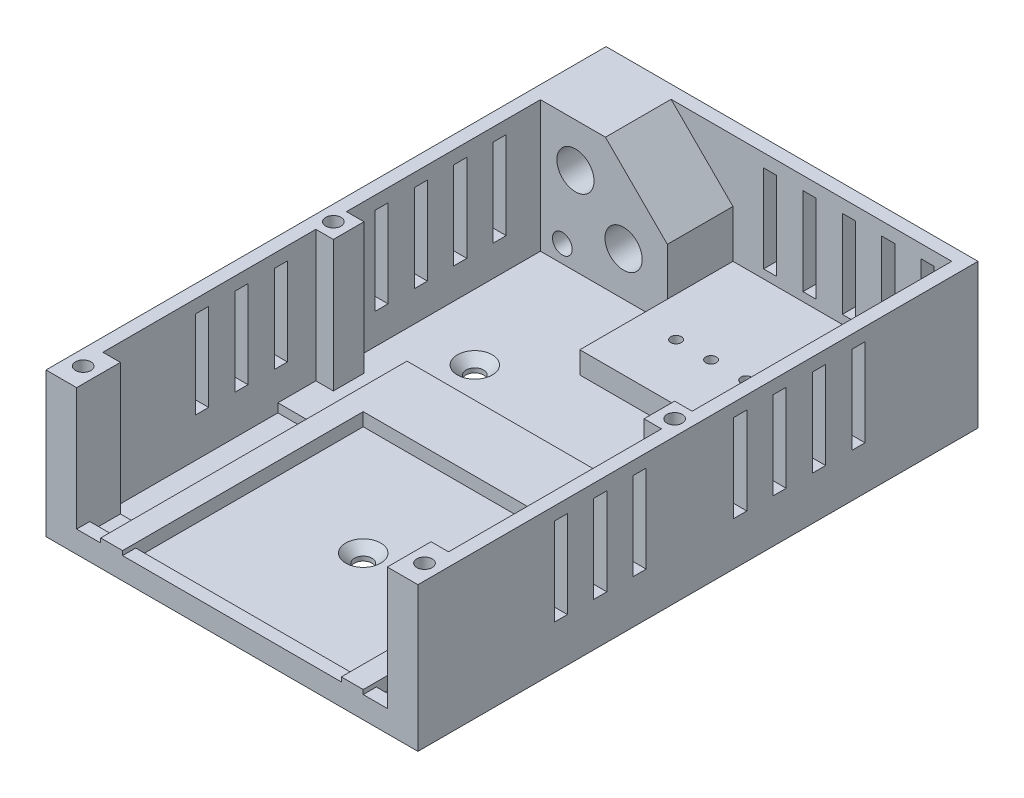
SolidWorks part; units mm, degrees
ref_plane "Front Plane" through (0, 0, 0) normal (0, 0, 1) x (1, 0, 0)
ref_plane "Top Plane" through (0, 0, 0) normal (0, 1, 0) x (1, 0, 0)
ref_plane "Right Plane" through (0, 0, 0) normal (1, 0, 0) x (0, 0, -1)
sketch "Sketch2" plane through (0, 0, 0) normal (0, 1, 0) x (1, 0, 0)
  line L1 (39.5, -62.5) -> (-39.5, -62.5)
  line L2 (39.5, -62.5) -> (39.5, 62.5)
  line L3 (39.5, 62.5) -> (-39.5, 62.5)
  line L4 (-39.5, -62.5) -> (-39.5, 62.5)
  line L5 (39.5, -62.5) -> (-39.5, 62.5) construction
  line L6 (39.5, 62.5) -> (-39.5, -62.5) construction
  point P0 (0, 0)
  dimension "D1" = 79
  dimension "D2" = 125
extrude "Boss-Extrude1" add sketch "Sketch2" along normal blind 3
sketch "Sketch9" plane through (0, 0, 0) normal (0, 1, 0) x (1, 0, 0)
  line L2 (-39.5, 62.5) -> (-39.5, -62.5)
  line L3 (-39.5, -62.5) -> (-42.5, -62.5)
  line L4 (-42.5, 65.5) -> (-42.5, -62.5)
  line L6 (39.5, 62.5) -> (39.5, -62.5)
  line L7 (39.5, -62.5) -> (42.5, -62.5)
  line L8 (42.5, 65.5) -> (42.5, -62.5)
  line L9 (39.5, 62.5) -> (-39.5, 62.5)
  line L11 (42.5, 65.5) -> (-42.5, 65.5)
  dimension "D1" = 3
  dimension "D2" = 3
  dimension "D3" = 3
sketch "Sketch3" plane through (0, 3, 0) normal (0, 1, 0) x (1, 0, 0)
  line L0 (0, -62.5) -> (0, 62.5) construction
  line L1 (-39.5, -62.5) -> (39.5, -62.5) construction
  line L2 (39.5, 62.5) -> (-39.5, 62.5) construction
  line L4 (30, -62.5) -> (-30, -62.5)
  line L5 (30, -62.5) -> (30, 7.5)
  line L6 (30, 7.5) -> (-30, 7.5)
  line L7 (-30, -62.5) -> (-30, 7.5)
  line L8 (30, -62.5) -> (-30, 7.5) construction
  line L9 (30, 7.5) -> (-30, -62.5) construction
  point P6 (0, -27.5)
  dimension "D1" = 60
  dimension "D2" = 70
extrude "support" add sketch "Sketch3" along normal blind 3
sketch "Sketch4" plane through (0, 6, 0) normal (0, 1, 0) x (1, 0, 0)
  line L0 (-30, -62.5) -> (30, -62.5) construction
  line L1 (-25, -62.5) -> (25, -62.5)
  line L2 (-25, -62.5) -> (-25, -7.5)
  line L3 (-25, -7.5) -> (25, -7.5)
  line L4 (25, -62.5) -> (25, -7.5)
  line L5 (30, 7.5) -> (-30, 7.5) construction
  line L6 (30, -62.5) -> (30, 7.5) construction
  line L7 (-30, 7.5) -> (-30, -62.5) construction
  dimension "D1" = 15
  dimension "D2" = 5
  dimension "D3" = 5
extrude "remove plastic" cut sketch "Sketch4" against normal blind 3
sketch "Sketch5" plane through (0, 3, 0) normal (0, 1, 0) x (1, 0, 0)
  line L1 (-10.5, 62.5) -> (39.5, 62.5)
  line L2 (-10.5, 62.5) -> (-10.5, 27.5)
  line L3 (-10.5, 27.5) -> (39.5, 27.5)
  line L4 (39.5, 62.5) -> (39.5, 27.5)
  line L5 (39.5, -62.5) -> (39.5, 62.5) construction
  line L7 (30, -62.5) -> (39.5, -62.5) construction
  line L8 (39.5, 62.5) -> (-39.5, 62.5) construction
  dimension "D1" = 50
  dimension "D3" = 90
extrude "Boss-Extrude3" add sketch "Sketch5" along normal blind 5
sketch "Sketch6" plane through (0, 8, 0) normal (0, 1, 0) x (1, 0, 0)
  line L0 (-10.5, 40.5) -> (39.5, 40.5) construction
  line L3 (14.5, 62.5) -> (14.5, 27.5) construction
  line L4 (39.5, 62.5) -> (-10.5, 62.5) construction
  line L5 (-10.5, 27.5) -> (39.5, 27.5) construction
  line L8 (-10.5, 27.5) -> (39.5, 27.5) construction
  circle A0 centre (-1.5, 40.5) radius 1.2
  circle A1 centre (6.5, 40.5) radius 1.2
  circle A2 centre (14.5, 40.5) radius 1.2
  circle A3 centre (22.5, 40.5) radius 1.2
  circle A4 centre (30.5, 40.5) radius 1.2
  dimension "D1" = 2.4
  dimension "D2" = 8
  dimension "D3" = 8
  dimension "D4" = 8
  dimension "D5" = 8
  dimension "D6" = 13
extrude "Cut-Extrude2" cut sketch "Sketch6" against normal blind 5 draft 1
sketch "Sketch7" plane through (0, 3, 0) normal (0, 1, 0) x (1, 0, 0)
  line L0 (-39.5, 62.5) -> (-39.5, -62.5) construction
  line L1 (-10.5, 62.5) -> (-39.5, 62.5)
  line L2 (-10.5, 62.5) -> (-10.5, 47.5)
  line L3 (-10.5, 47.5) -> (-39.5, 47.5)
  line L4 (-39.5, 62.5) -> (-39.5, 47.5)
  dimension "D1" = 15
extrude "cable block" add sketch "Sketch7" along normal blind 30
extrude "walls" add sketch "Sketch9" along normal up to surface (33 mm away) up to face at (-25, 33, -55)
sketch "Sketch8" plane through (0, 0, -47.5) normal (0, 0, 1) x (1, 0, 0)
  line L0 (-10.5, 33) -> (-10.5, 8) construction
  line L2 (-39.5, 33) -> (-10.5, 33) construction
  line L4 (-39.5, 3) -> (-10.5, 3) construction
  line L5 (-39.5, 33) -> (-39.5, 3) construction
  circle A0 centre (-20.5, 13) radius 4.25
  circle A1 centre (-34.5, 7) radius 2.25
  circle A2 centre (-31.5, 23) radius 4.25
  dimension "D1" = 8.5
  dimension "D2" = 4.5
  dimension "D3" = 10
  dimension "D8" = 10
  dimension "D4" = 8
  dimension "D5" = 10
  dimension "D6" = 5
  dimension "D7" = 4
extrude "cable holes round" cut sketch "Sketch8" against normal blind 31
sketch "Sketch10" plane through (0, 3, 0) normal (0, 1, 0) x (1, 0, 0)
  line L0 (0, -62.5) -> (0, -7.5) construction
  line L1 (-25, -62.5) -> (25, -62.5) construction
  line L2 (25, -7.5) -> (-25, -7.5) construction
  line L3 (-35.5, -62.5) -> (35.5, -62.5) construction
  line L4 (39.5, -62.5) -> (39.5, 27.5) construction
  line L5 (-39.5, -62.5) -> (-35.5, -62.5)
  line L6 (-39.5, -62.5) -> (-39.5, -52.5)
  line L7 (-39.5, -52.5) -> (-35.5, -52.5)
  line L8 (-35.5, -62.5) -> (-35.5, -52.5)
  line L9 (35.5, -62.5) -> (39.5, -62.5)
  line L10 (35.5, -62.5) -> (35.5, -52.5)
  line L11 (35.5, -52.5) -> (39.5, -52.5)
  line L12 (39.5, -62.5) -> (39.5, -52.5)
  dimension "D1" = 71
  dimension "D2" = 10
  dimension "D3" = 10
extrude "Lid screw posts front" add sketch "Sketch10" along normal up to surface (30 mm away) up to face at (-2.1, 33, -10.1)
sketch "Sketch11" plane through (0, 0, -62.5) normal (0, 0, 1) x (1, 0, 0)
  line L0 (14.5, 18) -> (32.5, 18)
  line L1 (39.5, 33) -> (39.5, 8) construction
  line L2 (14.5, 8) -> (32.5, 8)
  line L5 (39.5, 8) -> (-10.5, 8) construction
  arc A0 (14.5, 18) -> (14.5, 8) centre (14.5, 13) ccw
  arc A1 (32.5, 8) -> (32.5, 18) centre (32.5, 13) ccw
  dimension "D1" = 7
  dimension "D2" = 10
  dimension "D3" = 10
  dimension "D4" = 18
extrude "Cable cutout" [suppressed] cut sketch "Sketch11" against normal up to surface (3 mm away)
sketch "Sketch12" plane through (0, 0, -47.5) normal (0, 0, 1) x (1, 0, 0)
  line L0 (-24.6421, 33) -> (-10.5, 18.8579)
  line L1 (-39.5, 33) -> (-10.5, 33) construction
  line L2 (-10.5, 33) -> (-10.5, 8) construction
  line L3 (-10.5, 18.8579) -> (-10.5, 33)
  line L4 (-10.5, 33) -> (-24.6421, 33)
  dimension "D1" = 45
  dimension "D2" = 20
extrude "remove Material" cut sketch "Sketch12" against normal up to surface (15 mm away) up to face at (14.5, 20.5, -62.5)
sketch "Sketch13" plane through (0, 3, 0) normal (0, 1, 0) x (1, 0, 0)
  line L0 (-39.5, 47.5) -> (-39.5, -52.5) construction
  line L1 (-39.5, -3.8301) -> (-35.5, -3.8301)
  line L2 (-39.5, -3.8301) -> (-39.5, 3.1699)
  line L3 (-39.5, 3.1699) -> (-35.5, 3.1699)
  line L4 (-35.5, -3.8301) -> (-35.5, 3.1699)
  line L5 (39.5, -52.5) -> (39.5, 27.5) construction
  line L6 (39.5, 3.1699) -> (35.5, 3.1699)
  line L7 (39.5, 3.1699) -> (39.5, -3.8301)
  line L8 (39.5, -3.8301) -> (35.5, -3.8301)
  line L9 (35.5, 3.1699) -> (35.5, -3.8301)
  dimension "D1" = 4
  dimension "D2" = 7
  dimension "D3" = 7
  dimension "D4" = 7
  dimension "D5" = 4
  dimension "D6" = 7
extrude "Lid screw posts back" add sketch "Sketch13" along normal up to surface (30 mm away) up to face at (-3.5203, 33, 7.7857)
sketch "Sketch14" plane through (0, 33, 0) normal (0, 1, 0) x (1, 0, 0)
  line L0 (-35.5, -62.5) -> (-42.5, -62.5) construction
  line L2 (42.5, -62.5) -> (35.5, -62.5) construction
  line L3 (42.5, 65.5) -> (42.5, -62.5) construction
  line L4 (39.5, -3.8301) -> (35.5, -3.8301) construction
  line L5 (-35.5, -3.8301) -> (-39.5, -3.8301) construction
  line L6 (-42.5, -62.5) -> (-42.5, 65.5) construction
  circle A0 centre (-39, -57.5) radius 1.75
  circle A1 centre (39, -57.5) radius 1.75
  circle A2 centre (39, -0.3301) radius 1.75
  circle A3 centre (-39, -0.3301) radius 1.75
  dimension "D1" = 3.5
  dimension "D2" = 5
  dimension "D3" = 3.5
  dimension "D4" = 5
  dimension "D5" = 3.5
  dimension "D6" = 3.5
  dimension "D7" = 3.5
  dimension "D8" = 3.5
  dimension "D9" = 3.5
extrude "Lid screw holes" cut sketch "Sketch14" against normal blind 20 draft 1
sketch "Sketch16" plane through (0, 3, 0) normal (0, 1, 0) x (1, 0, 0)
  line L0 (-30, 7.5) -> (-30, -62.5) construction
  line L1 (-39.5, -52.5) -> (-30, -52.5)
  line L2 (-39.5, -52.5) -> (-39.5, -12.5)
  line L3 (-39.5, -12.5) -> (-30, -12.5)
  line L4 (-30, -52.5) -> (-30, -12.5)
  line L5 (30, -62.5) -> (30, 7.5) construction
  line L6 (39.5, -52.5) -> (30, -52.5)
  line L7 (39.5, -52.5) -> (39.5, -12.5)
  line L8 (39.5, -12.5) -> (30, -12.5)
  line L9 (30, -52.5) -> (30, -12.5)
  dimension "D1" = 20
  dimension "D2" = 20
extrude "Sliders" cut sketch "Sketch16" against normal blind 2
sketch "Sketch17" plane through (0, 0, 62.5) normal (0, 0, 1) x (1, 0, 0)
  line L0 (35.5, 33) -> (35.5, 3) construction
  line L1 (-35.5, 3) -> (35.5, 3)
  line L2 (-35.5, 3) -> (-35.5, 5)
  line L3 (-35.5, 5) -> (35.5, 5)
  line L4 (35.5, 3) -> (35.5, 5)
  dimension "D1" = 2
extrude "Front Lip" add sketch "Sketch17" against normal blind 3
sketch "Sketch19" plane through (42.5, 0, 0) normal (1, 0, 0) x (0, 0, -1)
  line L0 (65.5, 20) -> (13.84, 20) construction
  line L1 (65.5, 33) -> (65.5, 0) construction
  line L2 (39.67, 20) -> (36.67, 20) construction
  line L7 (65.5, 33) -> (-62.5, 33) construction
  line L16 (33.67, 33) -> (33.67, 27.4267) construction
  line L17 (24.67, 33) -> (24.67, 27.4664) construction
  line L18 (39.67, 10) -> (36.67, 10)
  line L19 (36.67, 30) -> (36.67, 10)
  line L20 (39.67, 30) -> (39.67, 10)
  line L21 (39.67, 30) -> (36.67, 30)
  line L22 (27.67, 30) -> (27.67, 10)
  line L23 (27.67, 10) -> (30.67, 10)
  line L24 (30.67, 30) -> (30.67, 10)
  line L25 (27.67, 30) -> (30.67, 30)
  line L26 (21.67, 30) -> (18.67, 30)
  line L27 (21.67, 10) -> (18.67, 10)
  line L28 (18.67, 30) -> (18.67, 10)
  line L29 (21.67, 30) -> (21.67, 10)
  line L30 (15.67, 33) -> (15.67, 27.5061) construction
  line L31 (9.67, 10) -> (12.67, 10)
  line L32 (9.67, 30) -> (9.67, 10)
  line L33 (12.67, 30) -> (12.67, 10)
  line L34 (9.67, 30) -> (12.67, 30)
  line L35 (-0.33, 20.9955) -> (-0.33, 33) construction
  line L36 (-10.33, 10) -> (-13.33, 10)
  line L37 (-13.33, 30) -> (-13.33, 10)
  line L38 (-10.33, 30) -> (-10.33, 10)
  line L39 (-10.33, 30) -> (-13.33, 30)
  line L40 (-16.33, 33) -> (-16.33, 27.6473) construction
  line L41 (-22.33, 10) -> (-19.33, 10)
  line L42 (-19.33, 30) -> (-19.33, 10)
  line L43 (-22.33, 30) -> (-22.33, 10)
  line L44 (-22.33, 30) -> (-19.33, 30)
  line L45 (-25.33, 33) -> (-25.33, 25.5009) construction
  line L46 (-28.33, 10) -> (-31.33, 10)
  line L47 (-31.33, 30) -> (-31.33, 10)
  line L48 (-28.33, 30) -> (-28.33, 10)
  line L49 (-28.33, 30) -> (-31.33, 30)
  dimension "D2" = 62.17
  dimension "D3" = 13
  dimension "D4" = 20
  dimension "D5" = 3
  dimension "D7" = 3
  dimension "D8" = 3
  dimension "D9" = 3
  dimension "D10" = 10
  dimension "D11" = 3
  dimension "D12" = 3
extrude "Vents Sides" cut sketch "Sketch19" against normal up to surface (85 mm away) up to face at (-42.5, 16.5, -1.5)
sketch "Sketch22" plane through (0, 0, -65.5) normal (0, 0, -1) x (-1, 0, 0)
  line L0 (-29.5, 33) -> (-29.5, 27.4554) construction
  line L1 (-35.5, 30) -> (-32.5, 30)
  line L2 (-35.5, 30) -> (-35.5, 10)
  line L3 (-35.5, 10) -> (-32.5, 10)
  line L4 (-32.5, 30) -> (-32.5, 10)
  line L5 (-42.5, 20) -> (42.5, 20) construction
  line L6 (-42.5, 33) -> (-42.5, 0) construction
  line L7 (42.5, 33) -> (42.5, 0) construction
  line L8 (42.5, 33) -> (-42.5, 33) construction
  line L9 (-35.5, 20) -> (-32.5, 20) construction
  line L10 (-11.5, 33) -> (-11.5, 27.4554) construction
  line L11 (-5.5, 10) -> (-8.5, 10)
  line L12 (-20.5, 33) -> (-20.5, 27.965) construction
  line L13 (-23.5, 10) -> (-26.5, 10)
  line L14 (-26.5, 30) -> (-26.5, 10)
  line L15 (-23.5, 30) -> (-23.5, 10)
  line L16 (-23.5, 30) -> (-26.5, 30)
  line L17 (-17.5, 10) -> (-14.5, 10)
  line L18 (-17.5, 30) -> (-17.5, 10)
  line L19 (-14.5, 30) -> (-14.5, 10)
  line L20 (-17.5, 30) -> (-14.5, 30)
  line L21 (-8.5, 30) -> (-8.5, 10)
  line L22 (-5.5, 30) -> (-5.5, 10)
  line L23 (-5.5, 30) -> (-8.5, 30)
  line L24 (-2.5, 33) -> (-2.5, 27.4554) construction
  line L25 (0.5, 10) -> (3.5, 10)
  line L26 (3.5, 30) -> (3.5, 10)
  line L27 (0.5, 30) -> (0.5, 10)
  line L28 (0.5, 30) -> (3.5, 30)
  dimension "D1" = 13
  dimension "D2" = 7
  dimension "D3" = 3
  dimension "D4" = 20
  dimension "D5" = 3
  dimension "D6" = 3
  dimension "D7" = 3
  dimension "D8" = 3
extrude "Vents Back" cut sketch "Sketch22" against normal up to surface (3 mm away) up to face at (6.6716, 20.1716, -62.5)
sketch "Sketch20" plane through (0, 3, 0) normal (0, 1, 0) x (1, 0, 0)
  line L1 (-42.5, -62.5) -> (42.5, -62.5) construction
  line L3 (-39.5, 47.5) -> (-39.5, 3.1699) construction
  line L4 (39.5, 3.1699) -> (39.5, 27.5) construction
  line L5 (-10.5, 27.5) -> (39.5, 27.5) construction
  circle A0 centre (0, -32.5) radius 2
  circle A1 centre (-24.5, 17.5) radius 2
  circle A2 centre (24.5, 17.5) radius 2
  point P6 (0, -62.5)
  dimension "D1" = 4
  dimension "D2" = 30
  dimension "D4" = 15
  dimension "D5" = 15
  dimension "D6" = 10
extrude "Cut-Extrude4" cut sketch "Sketch20" against normal up to surface (3 mm away) up to face at (0, 0, -1.5)
sketch "Sketch21" plane through (0, 3, 0) normal (0, 1, 0) x (1, 0, 0)
  circle A0 centre (-24.5, 17.5) radius 4
  circle A1 centre (0, -32.5) radius 4
  circle A2 centre (24.5, 17.5) radius 4
  dimension "D1" = 8
extrude "Cut-Extrude5" cut sketch "Sketch21" against normal blind 3 draft 45
equation "\"c_outside_width\"= 75mm"
equation "\"c_total_length\"= 80mm"
equation "\"c_inside_width\"= 70mm"
equation "\"wall_thickness\"= 3mm"
equation "\"D1@Sketch2\"=\"c_outside_width\" + \"wall_thickness\" + 1"
equation "\"D1@Boss-Extrude1\"=\"wall_thickness\""
equation "\"c_bottom_support_width\"=60"
equation "\"D1@Sketch3\"=\"c_bottom_support_width\""
equation "\"c_bottom_support_length\"=70"
equation "\"D2@Sketch3\"=\"c_bottom_support_length\""
equation "\"c_bottom_support_height\"= 3mm"
equation "\"D1@support\"=\"c_bottom_support_height\""
equation "\"D1@remove plastic\"=\"c_bottom_support_height\""
equation "\"D1@Sketch9\"=\"wall_thickness\""
equation "\"D2@Sketch9\"=\"wall_thickness\""
equation "\"D3@Sketch9\"=\"wall_thickness\""
equation "\"c__outside_height\"= 34.5mm"
equation "\"c_inside_height\"= 30mm"
equation "\"D1@walls\"=\"c__outside_height\""
equation "\"D1@Sketch10\"=\"c_inside_width\"+1"
equation "\"case_screw_diameter\"=3.5"
equation "\"D1@Sketch14\"=\"case_screw_diameter\""
equation "\"D1@cable block\" = \"c_inside_height\""
